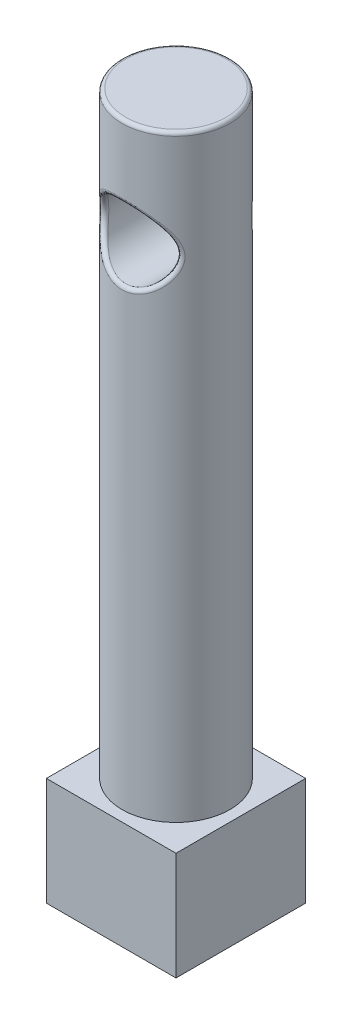
SolidWorks part; units mm, degrees
ref_plane "Plan de face" through (0, 0, 0) normal (0, 0, 1) x (1, 0, 0)
ref_plane "Plan de dessus" through (0, 0, 0) normal (0, 1, 0) x (1, 0, 0)
ref_plane "Plan de droite" through (0, 0, 0) normal (1, 0, 0) x (0, 0, -1)
sketch "Esquisse1" plane through (0, 0, 0) normal (0, 1, 0) x (1, 0, 0)
  circle A0 centre (0, 0) radius 1.5
extrude "Boss.-Extru.1" add sketch "Esquisse1" along normal blind 16.6
sketch "Esquisse2" plane through (0, 0, 0) normal (0, 0, 1) x (1, 0, 0)
  circle A0 centre (0, 13.6) radius 1
  point P2 (4.2184, 11.2341)
  dimension "D3" = 2
  dimension "D1" = 13.6
  dimension "D2" = 0
extrude "Enlèv. mat.-Extru.1" cut sketch "Esquisse2" against normal through all both and the other way through all
fillet "Congé1" radius 0.1 3 edges at (0, 16.6, 1.5) (0.1368, 12.6094, -1.4937) (-0.9782, 13.8075, 1.1371)
sketch "Esquisse3" plane through (0, 0, 0) normal (0, 1, 0) x (1, 0, 0)
  line L1 (1.8, 1.8) -> (-1.8, 1.8)
  line L2 (1.8, 1.8) -> (1.8, -1.8)
  line L3 (1.8, -1.8) -> (-1.8, -1.8)
  line L4 (-1.8, 1.8) -> (-1.8, -1.8)
  line L5 (1.8, 1.8) -> (-1.8, -1.8) construction
  line L6 (1.8, -1.8) -> (-1.8, 1.8) construction
  point P0 (0, 0)
  dimension "D1" = 1.8
  dimension "D2" = 1.8
extrude "Boss.-Extru.2" add sketch "Esquisse3" against normal blind 3
